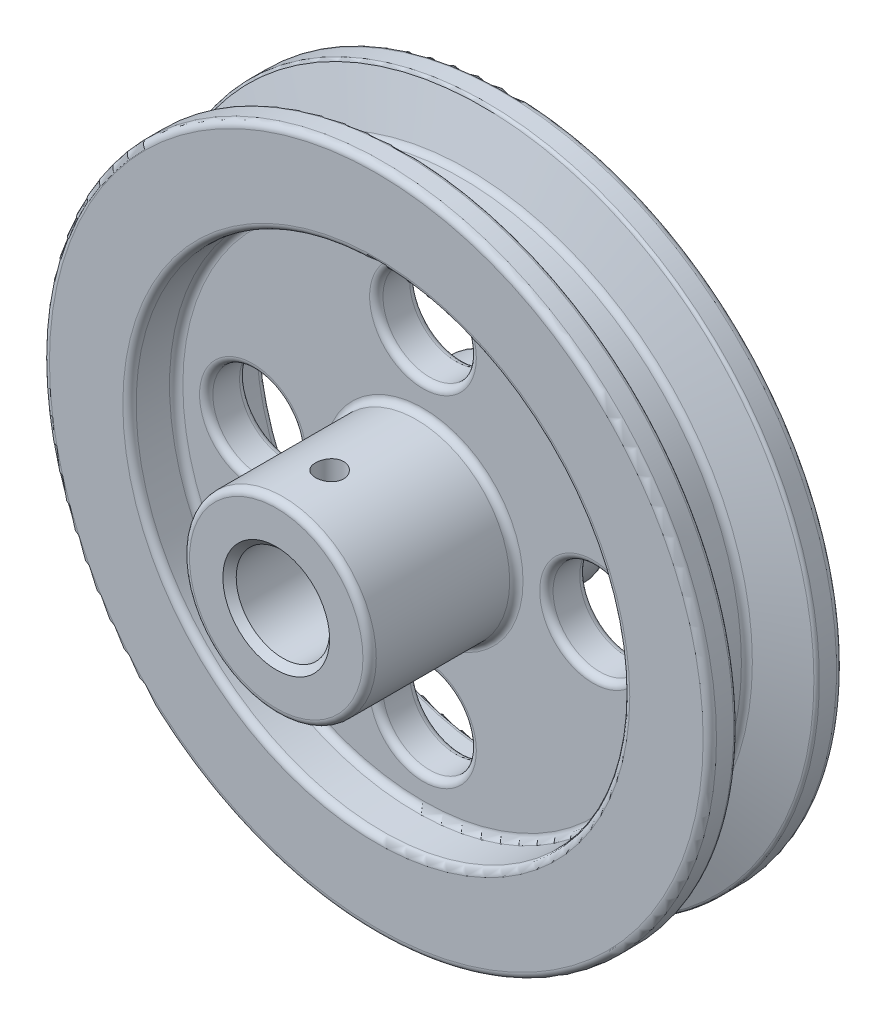
SolidWorks part; units mm, degrees
ref_plane "前基準面" through (0, 0, 0) normal (0, 0, 1) x (1, 0, 0)
ref_plane "上基準面" through (0, 0, 0) normal (0, 1, 0) x (1, 0, 0)
ref_plane "右基準面" through (0, 0, 0) normal (1, 0, 0) x (0, 0, -1)
sketch "草圖1" plane through (0, 0, 0) normal (1, 0, 0) x (0, 0, -1)
  line L0 (0, 0) -> (-77.9032, 0) construction
  line L1 (0, 0) -> (0, 82.9378) construction
  line L2 (-3, 14) -> (-3, 37)
  line L3 (12, 7) -> (-25, 7)
  line L4 (12, 7) -> (12, 14)
  line L5 (-25, 14) -> (-3, 14)
  line L6 (-25, 7) -> (-25, 14)
  line L8 (10, 37) -> (10, 50)
  line L9 (10, 50) -> (-10, 50)
  line L10 (-10, 37) -> (-10, 50)
  line L11 (-3, 37) -> (-10, 37)
  line L12 (3, 14) -> (3, 37)
  line L13 (3, 14) -> (12, 14)
  line L14 (3, 37) -> (10, 37)
  point P14 (0, 50)
  dimension "D1" = 20
  dimension "D2" = 37
  dimension "D3" = 14
  dimension "D4" = 28
  dimension "D5" = 74
  dimension "D6" = 100
  dimension "D7" = 9
  dimension "D8" = 22
revolve "旋轉1" add sketch "草圖1" angle 360 about L0
sketch "草圖3" plane through (0, 0, 0) normal (1, 0, 0) x (0, 0, -1)
  line L0 (0, 0) -> (29.5945, 0) construction
  line L1 (0, 0) -> (0, 62.2794) construction
  line L2 (-6.0621, 50) -> (6.0621, 50)
  line L3 (10, 50) -> (-10, 50) construction
  line L4 (6.0621, 50) -> (3.4628, 42)
  line L5 (3.4628, 42) -> (-3.4628, 42)
  line L6 (-6.0621, 50) -> (-3.4628, 42)
  line L7 (-4.6, 45.5) -> (4.6, 45.5) construction
  point P11 (0, 42)
  point P12 (0, 50)
  dimension "D1" = 8
  dimension "D2" = 4.5
  dimension "D3" = 36
  dimension "D4" = 9.2
revolve "除料-旋轉1" cut sketch "草圖3" angle 360 about L0
sketch "草圖4" plane through (0, 0, 3) normal (0, 0, 1) x (1, 0, 0)
  circle A0 centre (0, 0) radius 25.5 construction
  circle A1 centre (0, 25.5) radius 7
  circle A2 centre (25.5, 0) radius 7
  circle A3 centre (0, -25.5) radius 7
  circle A4 centre (-25.5, 0) radius 7
  dimension "D1" = 51
  dimension "D2" = 14
extrude "除料-伸長1" cut sketch "草圖4" against normal through all
chamfer "導角1" distance 1 angle 45 1 edges at (-7, 0, 25)
sketch "草圖5" plane through (0, 0, 0) normal (1, 0, 0) x (0, 0, -1)
  line L0 (-17, 14) -> (-17, 0) construction
  line L1 (-3, 14) -> (-25, 14) construction
  line L2 (-25, 14) -> (-25, -14) construction
  dimension "D1" = 8
hole_wizard "M5 螺紋孔1" positions "3D草圖1" profile "草圖6" tap size "M5" standard "ISO"
sketch3d "3D草圖1"
  point P0 (0, 14, 17)
sketch "草圖6" plane through (0, 14, 17) normal (1, 0, 0) x (0, 0, 1)
  line L0 (0, 0) -> (0, 7)
  line L1 (0, 7) -> (2.1, 7)
  line L2 (2.1, 7) -> (2.1, 0)
  line L5 (2.1, 0) -> (0, 0)
  line L11 (0, -6.35) -> (0, 107.95) construction
  dimension "貫穿螺孔鑽直徑" = 4.2
  dimension "貫穿螺孔鑽深度" = 7
cosmetic thread "鑽孔螺紋1" parameters "D2"=5
fillet "圓角1" radius 1 20 edges at (42, 0, 3.4628) (-37, 0, -10) (-50, 0, -10) (-14, 0, -3) (-37, 0, -3) (-7, 25.5, -3) (18.5, 0, -3) (-7, -25.5, -3) (-32.5, 0, -3) (-37, 0, 3) (-14, 0, 3) (7, 25.5, 3) (32.5, 0, 3) (7, -25.5, 3) (-18.5, 0, 3) (-14, 0, -12) (-14, 0, 25) (42, 0, -3.4628) (-50, 0, 10) (-37, 0, 10)
fillet "圓角2" radius 0.5 2 edges at (50, 0, -6.0621) (50, 0, 6.0621)
